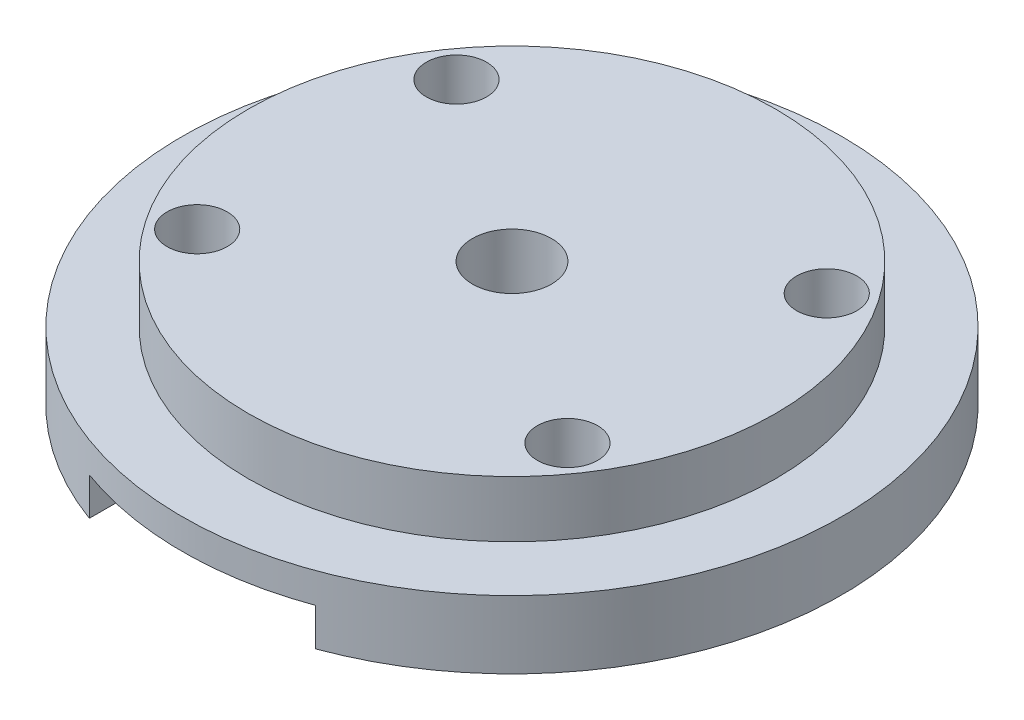
SolidWorks part; units mm, degrees
material "ABS"
ref_plane "正面" through (0, 0, 0) normal (0, 0, 1) x (1, 0, 0)
ref_plane "平面" through (0, 0, 0) normal (0, 1, 0) x (1, 0, 0)
ref_plane "右側面" through (0, 0, 0) normal (1, 0, 0) x (0, 0, -1)
sketch "ｽｹｯﾁ1" plane through (0, 0, 0) normal (0, 1, 0) x (1, 0, 0)
  circle A0 centre (0, 0) radius 2.1
  circle A1 centre (0, 0) radius 14
  dimension "D1" = 28
  dimension "D2" = 4.2
extrude "ﾎﾞｽ - 押し出し1" add sketch "ｽｹｯﾁ1" along normal blind 3
sketch "ｽｹｯﾁ3" plane through (0, 0, 0) normal (0, -1, 0) x (1, 0, 0)
  circle A0 centre (0, 0) radius 17.5
  circle A3 centre (0, 0) radius 2.1 construction
  circle A4 centre (0, 0) radius 2.1
  dimension "D1" = 35
extrude "ﾎﾞｽ - 押し出し2" add sketch "ｽｹｯﾁ3" along normal blind 1.6
sketch "ｽｹｯﾁ7" plane through (0, -1.6, 0) normal (0, -1, 0) x (1, 0, 0)
  line L0 (-6, 16.4393) -> (-6, -16.4393)
  line L1 (0, -55) -> (0, 55) construction
  line L2 (6, 16.4393) -> (6, -16.4393)
  circle A0 centre (0, 0) radius 17.5 construction
  arc A1 (-6, 16.4393) -> (-6, -16.4393) centre (0, 0) ccw
  arc A2 (6, 16.4393) -> (6, -16.4393) centre (0, 0) cw
  dimension "D1" = 12
extrude "ﾎﾞｽ - 押し出し5" add sketch "ｽｹｯﾁ7" along normal blind 2
sketch "ｽｹｯﾁ8" plane through (0, -3.6, 0) normal (0, -1, 0) x (1, 0, 0)
  line L0 (0, 0) -> (0, -17.5) construction
  line L2 (9.8298, 6.8829) -> (-9.8298, -6.8829) construction
  circle A0 centre (9.8298, 6.8829) radius 1.6
  circle A1 centre (-9.8298, -6.8829) radius 1.6
  arc A2 (-6, -16.4393) -> (6, -16.4393) centre (0, 0) ccw construction
  circle A3 centre (-9.8298, -6.8829) radius 3 construction
  circle A4 centre (-9.8298, 6.8829) radius 1.6
  circle A5 centre (9.8298, -6.8829) radius 1.6
  dimension "D1" = 3.2
  dimension "D3" = 6
  dimension "D2" = 12
  dimension "D4" = 55
extrude "ｶｯﾄ - 押し出し2" cut sketch "ｽｹｯﾁ8" against normal through all
